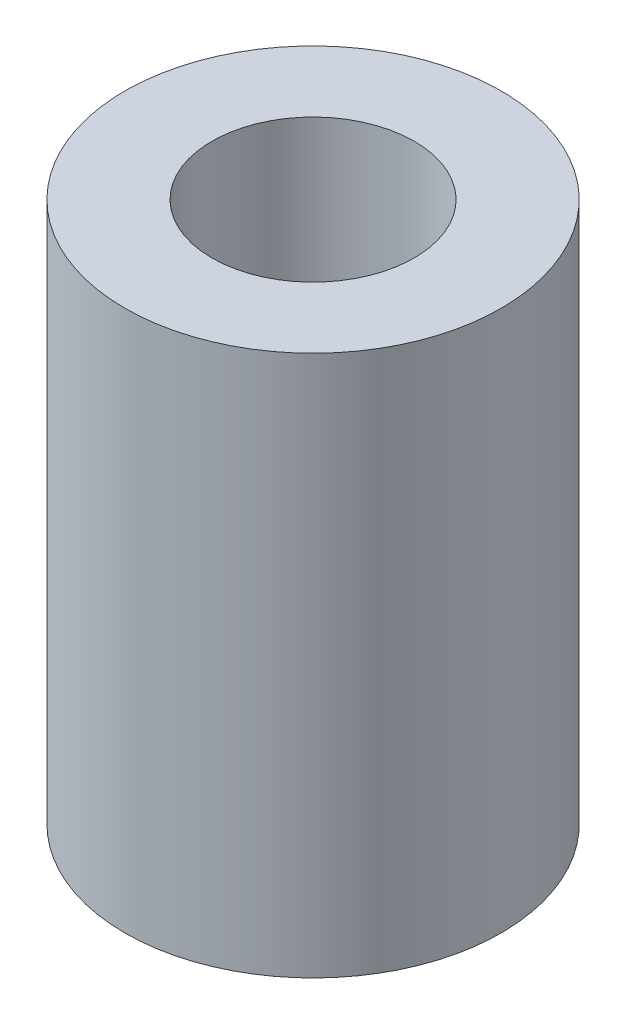
SolidWorks part; units mm, degrees
ref_plane "Спереди" through (0, 0, 0) normal (0, 0, 1) x (1, 0, 0)
ref_plane "Сверху" through (0, 0, 0) normal (0, 1, 0) x (1, 0, 0)
ref_plane "Справа" through (0, 0, 0) normal (1, 0, 0) x (0, 0, -1)
sketch "Эскиз1" plane through (0, 0, 0) normal (0, 1, 0) x (1, 0, 0)
  circle A0 centre (0, 0) radius 4
  circle A1 centre (0, 0) radius 2.15
  dimension "D1" = 4.3
  dimension "D2" = 8
extrude "тело" add sketch "Эскиз1" along normal blind 11.5
